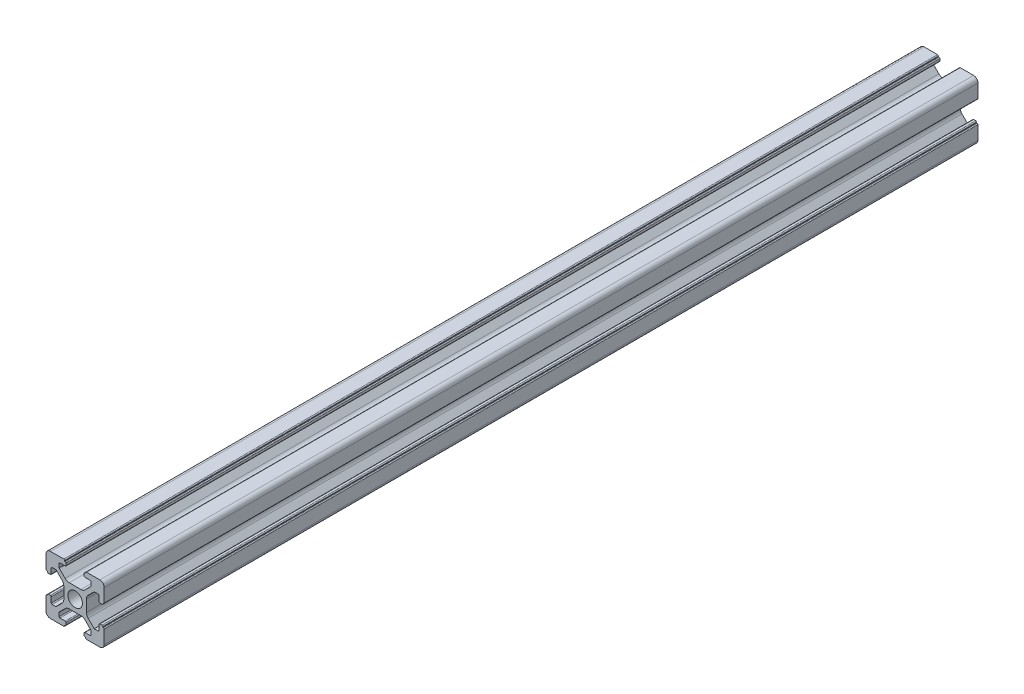
SolidWorks part; units mm, degrees
ref_plane "Front Plane" through (0, 0, 0) normal (0, 0, 1) x (1, 0, 0)
ref_plane "Top Plane" through (0, 0, 0) normal (0, 1, 0) x (1, 0, 0)
ref_plane "Right Plane" through (0, 0, 0) normal (1, 0, 0) x (0, 0, -1)
sketch "Model" plane through (0, 0, 0) normal (0, 0, 1) x (1, 0, 0)
  line L0 (3.9, 0) -> (3.9, -2.0109)
  line L1 (4.4858, -3.4251) -> (6.5607, -5.5)
  line L2 (6.5607, -5.5) -> (7.9, -5.5)
  line L3 (8.2, -5.2) -> (8.2, -3.4)
  line L4 (8.5, -3.1) -> (9.2, -3.1)
  line L5 (9.5, -3.4) -> (9.5, -3.6)
  line L6 (9.5, -3.6) -> (9.7, -3.6)
  line L7 (10, -3.9) -> (10, -8.5)
  line L8 (8.5, -10) -> (3.9, -10)
  line L9 (3.1, -9.2) -> (3.1, -8.5)
  line L10 (3.4, -8.2) -> (5.2, -8.2)
  line L11 (5.5, -7.9) -> (5.5, -6.6849)
  line L12 (5.4121, -6.4728) -> (3.4251, -4.4858)
  line L13 (2.0109, -3.9) -> (0, -3.9)
  line L14 (0, -3.9) -> (-2.0109, -3.9)
  line L15 (-3.4251, -4.4858) -> (-5.4121, -6.4728)
  line L16 (-5.5, -6.6849) -> (-5.5, -7.9)
  line L17 (-5.2, -8.2) -> (-3.4, -8.2)
  line L18 (-3.1, -8.5) -> (-3.1, -9.2)
  line L19 (-3.9, -10) -> (-8.5, -10)
  line L20 (-10, -8.5) -> (-10, -3.9)
  line L21 (-9.7, -3.6) -> (-9.5, -3.6)
  line L22 (-9.5, -3.6) -> (-9.5, -3.4)
  line L23 (-9.2, -3.1) -> (-8.5, -3.1)
  line L24 (-8.2, -3.4) -> (-8.2, -5.2)
  line L25 (-7.9, -5.5) -> (-6.6849, -5.5)
  line L26 (-6.4728, -5.4121) -> (-4.4858, -3.4251)
  line L27 (-3.9, -2.0109) -> (-3.9, 0)
  line L28 (-3.9, 0) -> (-3.9, 2.0109)
  line L29 (-4.4858, 3.4251) -> (-6.4728, 5.4121)
  line L30 (-6.6849, 5.5) -> (-7.9, 5.5)
  line L31 (-8.2, 5.2) -> (-8.2, 3.4)
  line L32 (-8.5, 3.1) -> (-9.2, 3.1)
  line L33 (-9.5, 3.4) -> (-9.5, 3.6)
  line L34 (-9.5, 3.6) -> (-9.7, 3.6)
  line L35 (-10, 3.9) -> (-10, 8.5)
  line L36 (-8.5, 10) -> (-3.9, 10)
  line L37 (-3.6, 9.7) -> (-3.6, 9.5)
  line L38 (-3.6, 9.5) -> (-3.4, 9.5)
  line L39 (-3.1, 9.2) -> (-3.1, 8.5)
  line L40 (-3.4, 8.2) -> (-5.2, 8.2)
  line L41 (-5.5, 7.9) -> (-5.5, 6.6849)
  line L42 (-5.4121, 6.4728) -> (-3.4251, 4.4858)
  line L43 (-2.0109, 3.9) -> (0, 3.9)
  line L44 (0, 3.9) -> (2.0109, 3.9)
  line L45 (3.4251, 4.4858) -> (5.4121, 6.4728)
  line L46 (5.5, 6.6849) -> (5.5, 7.9)
  line L47 (5.2, 8.2) -> (3.4, 8.2)
  line L48 (3.1, 8.5) -> (3.1, 9.2)
  line L49 (3.4, 9.5) -> (3.6, 9.5)
  line L50 (3.6, 9.5) -> (3.6, 9.7)
  line L51 (3.9, 10) -> (8.5, 10)
  line L52 (10, 8.5) -> (10, 3.9)
  line L53 (9.7, 3.6) -> (9.5, 3.6)
  line L54 (9.5, 3.6) -> (9.5, 3.4)
  line L55 (9.2, 3.1) -> (8.5, 3.1)
  line L56 (8.2, 3.4) -> (8.2, 5.2)
  line L57 (7.9, 5.5) -> (6.6849, 5.5)
  line L58 (6.4728, 5.4121) -> (4.4858, 3.4251)
  line L59 (3.9, 2.0109) -> (3.9, 0)
  circle A0 centre (0, 0) radius 2.5
  arc A1 (3.9, -2.0109) -> (4.4858, -3.4251) centre (5.9, -2.0109) ccw
  arc A2 (7.9, -5.5) -> (8.2, -5.2) centre (7.9, -5.2) ccw
  arc A3 (8.5, -3.1) -> (8.2, -3.4) centre (8.5, -3.4) ccw
  arc A4 (9.5, -3.4) -> (9.2, -3.1) centre (9.2, -3.4) ccw
  arc A5 (10, -3.9) -> (9.7, -3.6) centre (9.7, -3.9) ccw
  arc A6 (8.5, -10) -> (10, -8.5) centre (8.5, -8.5) ccw
  arc A7 (3.6, -9.7) -> (3.9, -10) centre (3.9, -9.7) ccw
  arc A8 (3.6, -9.7) -> (3.4, -9.5) centre (3.4, -9.7) ccw
  arc A9 (3.1, -9.2) -> (3.4, -9.5) centre (3.4, -9.2) ccw
  arc A10 (3.4, -8.2) -> (3.1, -8.5) centre (3.4, -8.5) ccw
  arc A11 (5.2, -8.2) -> (5.5, -7.9) centre (5.2, -7.9) ccw
  arc A12 (5.5, -6.6849) -> (5.4121, -6.4728) centre (5.2, -6.6849) ccw
  arc A13 (3.4251, -4.4858) -> (2.0109, -3.9) centre (2.0109, -5.9) ccw
  arc A14 (-2.0109, -3.9) -> (-3.4251, -4.4858) centre (-2.0109, -5.9) ccw
  arc A15 (-5.4121, -6.4728) -> (-5.5, -6.6849) centre (-5.2, -6.6849) ccw
  arc A16 (-5.5, -7.9) -> (-5.2, -8.2) centre (-5.2, -7.9) ccw
  arc A17 (-3.1, -8.5) -> (-3.4, -8.2) centre (-3.4, -8.5) ccw
  arc A18 (-3.4, -9.5) -> (-3.1, -9.2) centre (-3.4, -9.2) ccw
  arc A19 (-3.4, -9.5) -> (-3.6, -9.7) centre (-3.4, -9.7) ccw
  arc A20 (-3.9, -10) -> (-3.6, -9.7) centre (-3.9, -9.7) ccw
  arc A21 (-10, -8.5) -> (-8.5, -10) centre (-8.5, -8.5) ccw
  arc A22 (-9.7, -3.6) -> (-10, -3.9) centre (-9.7, -3.9) ccw
  arc A23 (-9.2, -3.1) -> (-9.5, -3.4) centre (-9.2, -3.4) ccw
  arc A24 (-8.2, -3.4) -> (-8.5, -3.1) centre (-8.5, -3.4) ccw
  arc A25 (-8.2, -5.2) -> (-7.9, -5.5) centre (-7.9, -5.2) ccw
  arc A26 (-6.6849, -5.5) -> (-6.4728, -5.4121) centre (-6.6849, -5.2) ccw
  arc A27 (-4.4858, -3.4251) -> (-3.9, -2.0109) centre (-5.9, -2.0109) ccw
  arc A28 (-3.9, 2.0109) -> (-4.4858, 3.4251) centre (-5.9, 2.0109) ccw
  arc A29 (-6.4728, 5.4121) -> (-6.6849, 5.5) centre (-6.6849, 5.2) ccw
  arc A30 (-7.9, 5.5) -> (-8.2, 5.2) centre (-7.9, 5.2) ccw
  arc A31 (-8.5, 3.1) -> (-8.2, 3.4) centre (-8.5, 3.4) ccw
  arc A32 (-9.5, 3.4) -> (-9.2, 3.1) centre (-9.2, 3.4) ccw
  arc A33 (-10, 3.9) -> (-9.7, 3.6) centre (-9.7, 3.9) ccw
  arc A34 (-8.5, 10) -> (-10, 8.5) centre (-8.5, 8.5) ccw
  arc A35 (-3.6, 9.7) -> (-3.9, 10) centre (-3.9, 9.7) ccw
  arc A36 (-3.1, 9.2) -> (-3.4, 9.5) centre (-3.4, 9.2) ccw
  arc A37 (-3.4, 8.2) -> (-3.1, 8.5) centre (-3.4, 8.5) ccw
  arc A38 (-5.2, 8.2) -> (-5.5, 7.9) centre (-5.2, 7.9) ccw
  arc A39 (-5.5, 6.6849) -> (-5.4121, 6.4728) centre (-5.2, 6.6849) ccw
  arc A40 (-3.4251, 4.4858) -> (-2.0109, 3.9) centre (-2.0109, 5.9) ccw
  arc A41 (2.0109, 3.9) -> (3.4251, 4.4858) centre (2.0109, 5.9) ccw
  arc A42 (5.4121, 6.4728) -> (5.5, 6.6849) centre (5.2, 6.6849) ccw
  arc A43 (5.5, 7.9) -> (5.2, 8.2) centre (5.2, 7.9) ccw
  arc A44 (3.1, 8.5) -> (3.4, 8.2) centre (3.4, 8.5) ccw
  arc A45 (3.4, 9.5) -> (3.1, 9.2) centre (3.4, 9.2) ccw
  arc A46 (3.9, 10) -> (3.6, 9.7) centre (3.9, 9.7) ccw
  arc A47 (10, 8.5) -> (8.5, 10) centre (8.5, 8.5) ccw
  arc A48 (9.7, 3.6) -> (10, 3.9) centre (9.7, 3.9) ccw
  arc A49 (9.2, 3.1) -> (9.5, 3.4) centre (9.2, 3.4) ccw
  arc A50 (8.2, 3.4) -> (8.5, 3.1) centre (8.5, 3.4) ccw
  arc A51 (8.2, 5.2) -> (7.9, 5.5) centre (7.9, 5.2) ccw
  arc A52 (6.6849, 5.5) -> (6.4728, 5.4121) centre (6.6849, 5.2) ccw
  arc A53 (4.4858, 3.4251) -> (3.9, 2.0109) centre (5.9, 2.0109) ccw
extrude "Boss-Extrude1" add sketch "Model" along normal blind 300
sketch "Sketch1" plane through (10, 0, 0) normal (1, 0, 0) x (0, 0, -1)
  line L0 (-300, -10) -> (0, -10) construction
  line L1 (0, -2.0109) -> (0, 2.0109) construction
  circle A0 centre (-150, 0) radius 2.4
  dimension "D1" = 4.8
  dimension "D2" = 10
  dimension "D3" = 150
extrude "Cut-Extrude1" cut sketch "Sketch1" against normal through all both and the other way through all
sketch "Sketch2" plane through (0, 3.9, 0) normal (0, 1, 0) x (1, 0, 0)
  line L0 (2.0109, 0) -> (-2.0109, 0) construction
  circle A0 centre (0, -15) radius 1.45
  dimension "D2" = 2.9
  dimension "D1" = 15
extrude "Cut-Extrude2" cut sketch "Sketch2" against normal blind 18
ref_plane "Plane1" through (0, 0, 150) normal (0, 0, -1) x (-1, 0, 0)
mirror "Mirror1" about plane through (0, 0, 150) normal (0, 0, -1) of "Cut-Extrude2"
sketch "Sketch5" plane through (0, -3.9, 0) normal (0, -1, 0) x (1, 0, 0)
  line L0 (-2.0109, 300) -> (2.0109, 300) construction
  line L1 (-10, 300) -> (-10, 0) construction
  circle A0 centre (0, 170) radius 1.5
  circle A1 centre (0, 130) radius 1.5
  point P4 (0, 0)
  point P7 (0, 300)
  point P8 (0, 0)
  point P12 (-10, 150)
  dimension "D1" = 3
  dimension "D2" = 40
  dimension "D3" = 20
extrude "Cut-Extrude4" cut sketch "Sketch5" against normal blind 58
